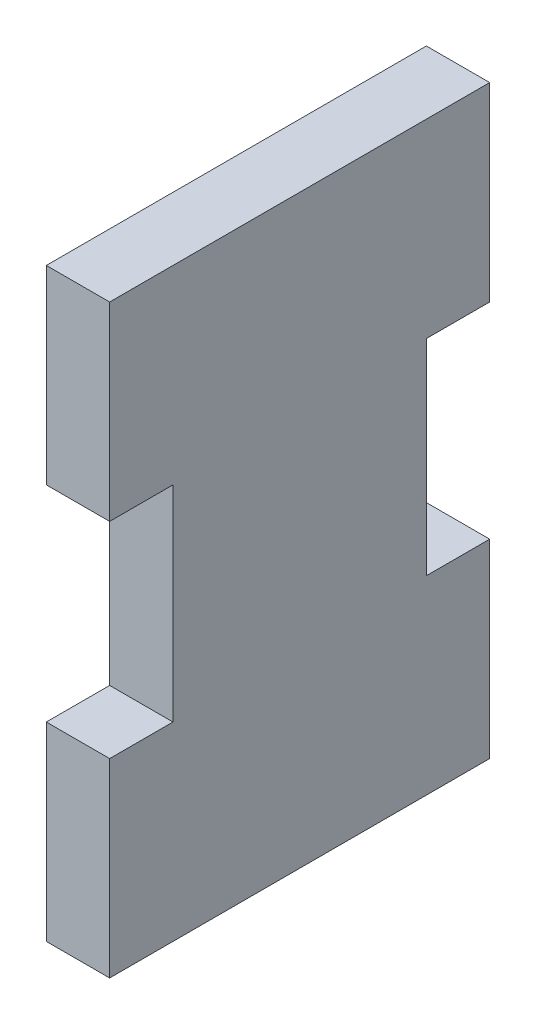
SolidWorks part; units mm, degrees
ref_plane "Front Plane" through (0, 0, 0) normal (0, 0, 1) x (1, 0, 0)
ref_plane "Top Plane" through (0, 0, 0) normal (0, 1, 0) x (1, 0, 0)
ref_plane "Right Plane" through (0, 0, 0) normal (1, 0, 0) x (0, 0, -1)
sketch "Sketch1" plane through (0, 0, 0) normal (0, 0, 1) x (1, 0, 0)
  line L1 (84.0208, 63.0814) -> (80.8458, 63.0814)
  line L2 (84.0208, 63.0814) -> (84.0208, 92.4261)
  line L3 (84.0208, 92.4261) -> (80.8458, 92.4261)
  line L4 (80.8458, 63.0814) -> (80.8458, 92.4261)
  dimension "D1" = 3.175
extrude "Boss-Extrude1" add sketch "Sketch1" against normal up to surface (19.05 mm away) contours L2 L3 L4 L1
sketch "Sketch2" plane through (84.0208, 0, 0) normal (1, 0, 0) x (0, 0, -1)
  line L0 (0, 63.0814) -> (0, 92.4261) construction
  line L1 (0, 72.6064) -> (3.175, 72.6064)
  line L2 (0, 72.6064) -> (0, 82.9011)
  line L3 (0, 82.9011) -> (3.175, 82.9011)
  line L4 (3.175, 72.6064) -> (3.175, 82.9011)
  line L5 (3.175, 70.9591) -> (3.175, 111.0627) construction
  line L6 (19.05, 92.4261) -> (19.05, 63.0814) construction
  line L7 (19.05, 82.9011) -> (15.875, 82.9011)
  line L8 (19.05, 82.9011) -> (19.05, 72.6064)
  line L9 (19.05, 72.6064) -> (15.875, 72.6064)
  line L10 (15.875, 82.9011) -> (15.875, 72.6064)
  line L11 (15.875, 111.0627) -> (15.875, 70.9591) construction
  line L12 (19.05, 92.4261) -> (0, 92.4261) construction
  line L13 (19.05, 63.0814) -> (0, 63.0814) construction
  dimension "D1" = 9.525
  dimension "D2" = 9.525
  dimension "D3" = 9.525
  dimension "D4" = 9.525
extrude "Cut-Extrude1" cut sketch "Sketch2" against normal blind 5.08
